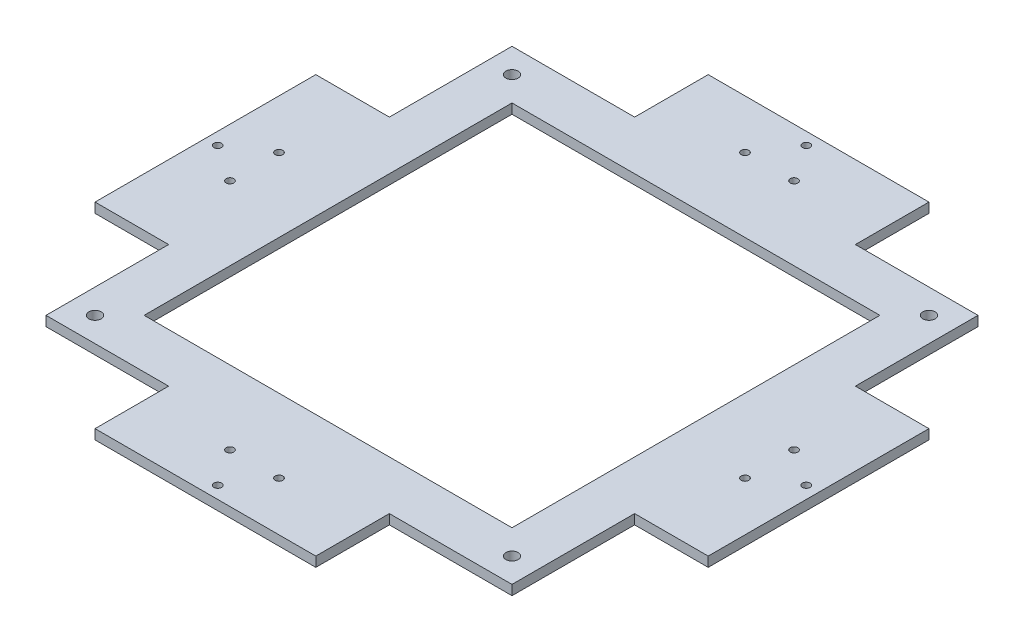
SolidWorks part; units mm, degrees
ref_plane "Alzado" through (0, 0, 0) normal (0, 0, 1) x (1, 0, 0)
ref_plane "Planta" through (0, 0, 0) normal (0, 1, 0) x (1, 0, 0)
ref_plane "Vista lateral" through (0, 0, 0) normal (1, 0, 0) x (0, 0, -1)
sketch "Croquis1" plane through (0, 0, 0) normal (0, 1, 0) x (1, 0, 0)
  line L0 (125, 40) -> (125, 0) construction
  line L1 (0, 0) -> (250, 0)
  line L2 (0, 0) -> (0, 250)
  line L3 (0, 250) -> (250, 250)
  line L4 (250, 0) -> (250, 250)
  line L5 (40, 40) -> (210, 40) construction
  line L6 (40, 40) -> (40, 210) construction
  line L7 (40, 210) -> (210, 210) construction
  line L8 (210, 40) -> (210, 210) construction
  line L9 (210, 125) -> (250, 125) construction
  circle A0 centre (40, 210) radius 2.5
  circle A1 centre (210, 210) radius 2.5
  circle A2 centre (210, 40) radius 2.5
  circle A3 centre (40, 40) radius 2.5
  dimension "D3" = 5
  dimension "D1" = 250
  dimension "D2" = 170
extrude "Saliente-Extruir1" add sketch "Croquis1" along normal blind 4
sketch "Croquis2" plane through (0, 4, 0) normal (0, 1, 0) x (1, 0, 0)
  line L0 (50, 125) -> (0, 125) construction
  line L1 (50, 50) -> (200, 50)
  line L2 (50, 50) -> (50, 150.0904)
  line L3 (50, 200) -> (200, 200)
  line L4 (200, 50) -> (200, 200)
  line L5 (0, 250) -> (0, 0) construction
  line L6 (125, 50) -> (125, 0) construction
  line L7 (0, 0) -> (250, 0) construction
  line L8 (50, 125) -> (200, 125) construction
  line L9 (125, 200) -> (125, 50) construction
  line L10 (48, 151.5) -> (48, 125) construction
  line L19 (50, 50) -> (200, 50) construction
  line L20 (50, 50) -> (50, 200) construction
  line L21 (50, 200) -> (200, 200) construction
  line L22 (200, 50) -> (200, 200) construction
  line L24 (50, 150.0904) -> (50, 172.9096)
  line L27 (59.9079, 125) -> (59.9079, 200) construction
  line L28 (50, 161.5) -> (34.9079, 161.5) construction
  line L29 (50, 150.0904) -> (125, 150.0904) construction
  line L30 (88.5, 200) -> (88.5, 125.0904) construction
  line L31 (78.5, 200) -> (98.5, 200)
  line L44 (121.5, 50) -> (101.5, 50)
  line L59 (88.5, 162.5452) -> (125, 162.5452) construction
  line L60 (42.454, 161.5) -> (42.454, 125) construction
  line L61 (25, 103.5) -> (25, 123.5) [skipped]
  line L65 (50, 150.0904) -> (50, 200)
  line L66 (125.0904, 175) -> (147.9096, 175) [skipped]
  line L69 (175, 146.5) -> (175, 126.5) [skipped]
  line L71 (150, 99.9096) -> (150, 77.0904) [skipped]
  line L72 (74.9096, 75) -> (52.0904, 75) [skipped]
  point P18 (50, 125)
  point P19 (125, 200)
  point P21 (0, 0)
  dimension "D1" = 150
  dimension "D2" = 150
  dimension "D4" = 4
  dimension "D6" = 36.5
extrude "Cortar-Extruir1" cut sketch "Croquis2" against normal blind 4
sketch "Croquis3" plane through (0, 4, 0) normal (0, 1, 0) x (1, 0, 0)
  line L0 (75, 175) -> (75, 75)
  line L1 (50, 200) -> (200, 200)
  line L2 (50, 200) -> (50, 50)
  line L3 (50, 50) -> (200, 50)
  line L4 (200, 200) -> (200, 50)
  line L5 (75, 75) -> (175, 75)
  line L6 (175, 175) -> (175, 75)
  line L7 (75, 175) -> (175, 175)
  dimension "D1" = 25
extrude "Saliente-Extruir2" add sketch "Croquis3" against normal up to surface (4 mm away) up to face at (125, 0, -125)
sketch "Croquis4" plane through (0, 4, 0) normal (0, 1, 0) x (1, 0, 0)
  line L0 (125, 0) -> (125, 75) construction
  line L1 (0, 0) -> (250, 0) construction
  line L2 (75, 75) -> (175, 75) construction
  line L3 (115, 20) -> (125, 20) construction
  line L4 (125, 20) -> (135, 20) construction
  circle A0 centre (115, 20) radius 1.55
  circle A1 centre (135, 20) radius 1.55
  circle A2 centre (125, 5) radius 1.55
  dimension "D1" = 3.1
  dimension "D4" = 5
  dimension "D2" = 10
  dimension "D3" = 20
extrude "Cortar-Extruir2" cut sketch "Croquis4" against normal blind 10
sketch "Croquis5" plane through (0, 4, 0) normal (0, 1, 0) x (1, 0, 0)
  line L0 (75, 175) -> (75, 75) construction
  line L1 (75, 75) -> (175, 75) construction
  line L2 (175, 75) -> (175, 175) construction
  line L3 (175, 175) -> (75, 175) construction
  line L4 (75, 175) -> (75, 75)
  line L5 (75, 75) -> (175, 75)
  line L6 (175, 75) -> (175, 175)
  line L7 (175, 175) -> (75, 175)
  line L8 (50, 200) -> (50, 50)
  line L9 (50, 50) -> (200, 50)
  line L10 (200, 50) -> (200, 200)
  line L11 (200, 200) -> (50, 200)
  dimension "D1" = 25
extrude "Cortar-Extruir3" cut sketch "Croquis5" against normal blind 10
sketch "Croquis6" plane through (0, 4, 0) normal (0, 1, 0) x (1, 0, 0)
  line L0 (250, 0) -> (250, 250) construction
  line L1 (250, 0) -> (170, 0)
  line L2 (250, 0) -> (250, 30)
  line L3 (250, 30) -> (170, 30)
  line L4 (170, 0) -> (170, 30)
  line L5 (220, 30) -> (250, 30)
  line L6 (220, 30) -> (220, 80)
  line L7 (220, 80) -> (250, 80)
  line L8 (250, 30) -> (250, 80)
  line L9 (50, 125) -> (200, 125) construction
  line L10 (50, 200) -> (50, 50) construction
  line L11 (200, 50) -> (200, 200) construction
  line L12 (125, 50) -> (125, 125) construction
  line L13 (50, 50) -> (200, 50) construction
  line L14 (0, 0) -> (30, 0)
  line L15 (0, 0) -> (0, 80)
  line L16 (0, 80) -> (30, 80)
  line L17 (30, 0) -> (30, 80)
  line L18 (30, 30) -> (80, 30)
  line L19 (30, 30) -> (30, 0)
  line L20 (30, 0) -> (80, 0)
  line L21 (80, 30) -> (80, 0)
  line L22 (0, 250) -> (0, 220)
  line L23 (0, 250) -> (80, 250)
  line L24 (80, 250) -> (80, 220)
  line L25 (0, 220) -> (80, 220)
  line L26 (30, 220) -> (30, 170)
  line L27 (30, 220) -> (0, 220)
  line L28 (0, 220) -> (0, 170)
  line L29 (30, 170) -> (0, 170)
  line L30 (250, 250) -> (220, 250)
  line L31 (250, 250) -> (250, 170)
  line L32 (250, 170) -> (220, 170)
  line L33 (220, 250) -> (220, 170)
  line L34 (220, 220) -> (170, 220)
  line L35 (220, 220) -> (220, 250)
  line L36 (220, 250) -> (170, 250)
  line L37 (170, 220) -> (170, 250)
  dimension "D1" = 30
  dimension "D2" = 80
  dimension "D3" = 80
  dimension "D4" = 4
extrude "Cortar-Extruir4" cut sketch "Croquis6" against normal blind 10 contours L2 L1 L4 L3 | L18 L21 L20 L19 | L14 L17 L16 L15 | L26 L29 L28 L27 | L22 L25 L24 L23 | L30 L33 L32 L31 | L34 L37 L36 L35 | L6 L5 L8 L7
sketch "Croquis8" plane through (0, 4, 0) normal (0, 1, 0) x (1, 0, 0)
  line L0 (50, 125) -> (200, 125) construction
  line L1 (50, 200) -> (50, 50) construction
  line L2 (200, 50) -> (200, 200) construction
  line L3 (125, 125) -> (125, 50) construction
  line L4 (50, 50) -> (200, 50) construction
  circle A0 centre (125, 5) radius 1.55 construction
  circle A1 centre (135, 20) radius 1.55 construction
  circle A2 centre (115, 20) radius 1.55 construction
  circle A3 centre (125, 5) radius 1.55
  circle A4 centre (135, 20) radius 1.55
  circle A5 centre (115, 20) radius 1.55
  circle A6 centre (20, 135) radius 1.55
  circle A7 centre (5, 125) radius 1.55
  circle A8 centre (20, 115) radius 1.55
  circle A9 centre (135, 230) radius 1.55
  circle A10 centre (125, 245) radius 1.55
  circle A11 centre (115, 230) radius 1.55
  circle A12 centre (230, 115) radius 1.55
  circle A13 centre (245, 125) radius 1.55
  circle A14 centre (230, 135) radius 1.55
  dimension "D1" = 4
extrude "Cortar-Extruir5" cut sketch "Croquis8" against normal blind 10
